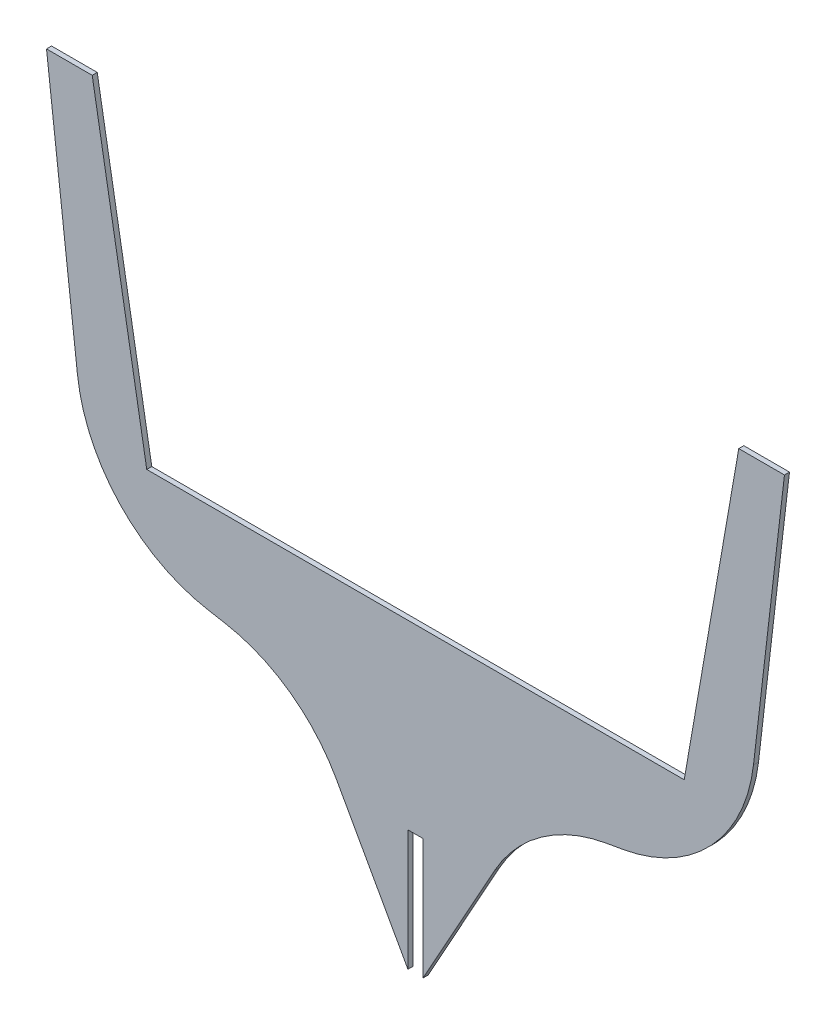
SolidWorks part; units mm, degrees
ref_plane "Plan de face" through (0, 0, 0) normal (0, 0, 1) x (1, 0, 0)
ref_plane "Plan de dessus" through (0, 0, 0) normal (0, 1, 0) x (1, 0, 0)
ref_plane "Plan de droite" through (0, 0, 0) normal (1, 0, 0) x (0, 0, -1)
sketch "Esquisse3" plane through (0, 0, 0) normal (0, 0, 1) x (1, 0, 0)
  line L46 (12.7059, 123.4436) -> (45.2342, -63.8313)
  line L48 (-14.5416, 123.4436) -> (12.0853, -105.7848)
  line L49 (12.0853, -105.7848) -> (136.3361, -127.6909)
  line L50 (136.3361, -127.6909) -> (200.9584, -244.0564)
  line L51 (200.9584, -244.0564) -> (200.9584, -172.0564)
  line L54 (205.4584, -172.0564) -> (205.4584, 18.2487) construction
  line L67 (-14.5416, 123.4436) -> (12.7059, 123.4436)
  line L68 (45.2342, -63.8313) -> (365.6827, -63.8313)
  line L69 (200.9584, -172.0564) -> (209.9584, -172.0564)
  line L70 (425.4584, 123.4436) -> (398.2109, 123.4436)
  line L71 (209.9584, -244.0564) -> (209.9584, -172.0564)
  line L72 (274.5808, -127.6909) -> (209.9584, -244.0564)
  line L73 (398.8316, -105.7848) -> (274.5808, -127.6909)
  line L74 (425.4584, 123.4436) -> (398.8316, -105.7848)
  line L75 (398.2109, 123.4436) -> (365.6827, -63.8313)
  point P6 (205.4584, -63.8313)
  point P16 (57.9997, 63.6572)
  point P17 (-21.8235, -154.8228)
  point P18 (56.6782, -128.6556)
  point P19 (0, -114.4816)
  point P20 (62.1298, -101.398)
  point P21 (300.6175, -198.9217)
  point P23 (136.3361, -165.1909)
  point P24 (0, -108.3483)
  point P25 (12.7059, 121.3073)
  point P26 (408.8316, -105.7848)
  point P27 (45.2342, -63.8313)
  dimension "D1" = 440
  dimension "D2" = 9
  dimension "D3" = 295.5
  dimension "D4" = 72
  dimension "D5" = 108.2251
extrude "Boss.-Extru.3" add sketch "Esquisse3" along normal blind 3
fillet "Congé1" radius 95 4 edges at (398.8316, -105.7848, 1.5) (274.5808, -127.6909, 1.5) (136.3361, -127.6909, 1.5) (12.0853, -105.7848, 1.5)
